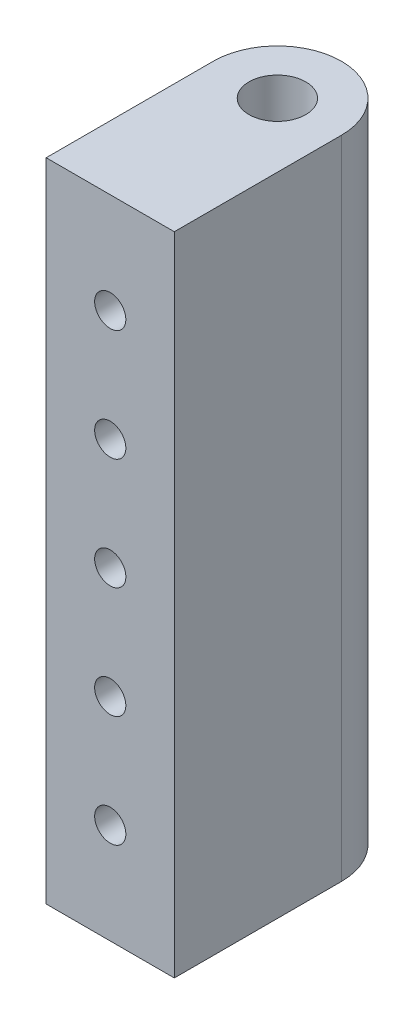
SolidWorks part; units mm, degrees
material "ABS"
ref_plane "Front Plane" through (0, 0, 0) normal (0, 0, 1) x (1, 0, 0)
ref_plane "Top Plane" through (0, 0, 0) normal (0, 1, 0) x (1, 0, 0)
ref_plane "Right Plane" through (0, 0, 0) normal (1, 0, 0) x (0, 0, -1)
sketch "Sketch1" plane through (0, 0, 0) normal (0, 1, 0) x (1, 0, 0)
  line L0 (-5.75, 0) -> (-5.75, -15)
  line L1 (-5.75, -15) -> (5.75, -15)
  line L2 (5.75, -15) -> (5.75, 0)
  circle A0 centre (0, 0) radius 2.55
  arc A1 (5.75, 0) -> (-5.75, 0) centre (0, 0) ccw
  dimension "D1" = 5.1
  dimension "D2" = 11.5
  dimension "D3" = 15
extrude "Boss-Extrude1" add sketch "Sketch1" along normal blind 58
sketch "Sketch2" plane through (0, 0, 15) normal (0, 0, 1) x (1, 0, 0)
  line L0 (0, 58) -> (0, 0) construction
  line L1 (-5.75, 58) -> (5.75, 58) construction
  circle A1 centre (0, 49) radius 1.4
  circle A2 centre (0, 39) radius 1.4
  circle A3 centre (0, 29) radius 1.4
  circle A4 centre (0, 19) radius 1.4
  circle A5 centre (0, 9) radius 1.4
  dimension "D1" = 9
  dimension "D2" = 2.8
  dimension "D3" = 5
extrude "Cut-Extrude1" cut sketch "Sketch2" against normal blind 10
